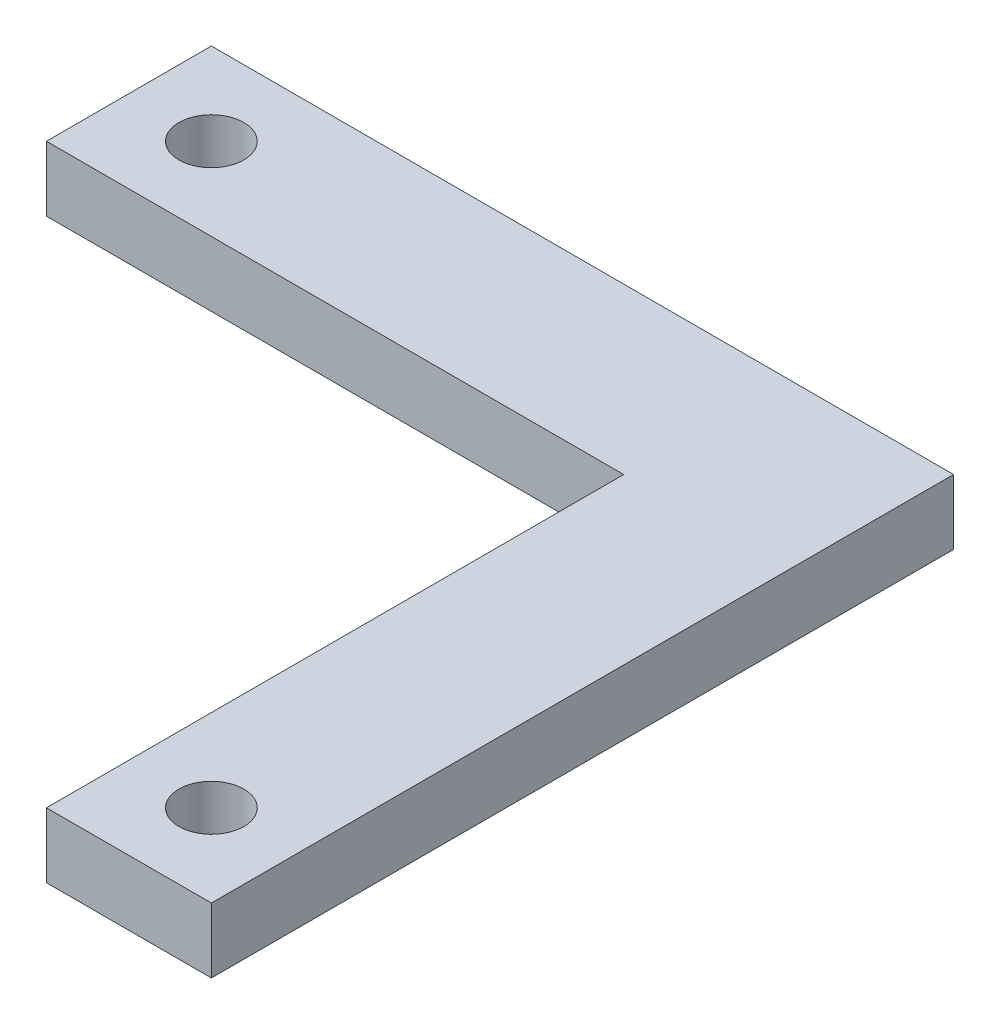
SolidWorks part; units mm, degrees
ref_plane "Front Plane" through (0, 0, 0) normal (0, 0, 1) x (1, 0, 0)
ref_plane "Top Plane" through (0, 0, 0) normal (0, 1, 0) x (1, 0, 0)
ref_plane "Right Plane" through (0, 0, 0) normal (1, 0, 0) x (0, 0, -1)
sketch "Sketch1" plane through (0, 0, 0) normal (0, 1, 0) x (1, 0, 0)
  line L0 (0, 6.35) -> (6.35, 6.35)
  line L2 (0, 0) -> (0, 12.7)
  line L3 (0, 12.7) -> (57.15, 12.7)
  line L4 (57.15, 0) -> (57.15, 12.7)
  line L5 (50.8, -44.45) -> (50.8, -38.1)
  line L7 (44.45, 0) -> (44.45, -44.45)
  line L8 (44.45, -44.45) -> (57.15, -44.45)
  line L9 (57.15, -44.45) -> (57.15, 0)
  line L10 (44.45, 0) -> (0, 0)
  circle A0 centre (6.35, 6.35) radius 2.5
  circle A2 centre (50.8, -38.1) radius 2.5
  dimension "D4" = 5
  dimension "D6" = 6.35
  dimension "D8" = 5
  dimension "D1" = 57.15
  dimension "D2" = 12.7
  dimension "D3" = 6.35
  dimension "D5" = 12.7
  dimension "D7" = 44.45
  dimension "D9" = 12.7
extrude "Boss-Extrude1" add sketch "Sketch1" along normal blind 5
